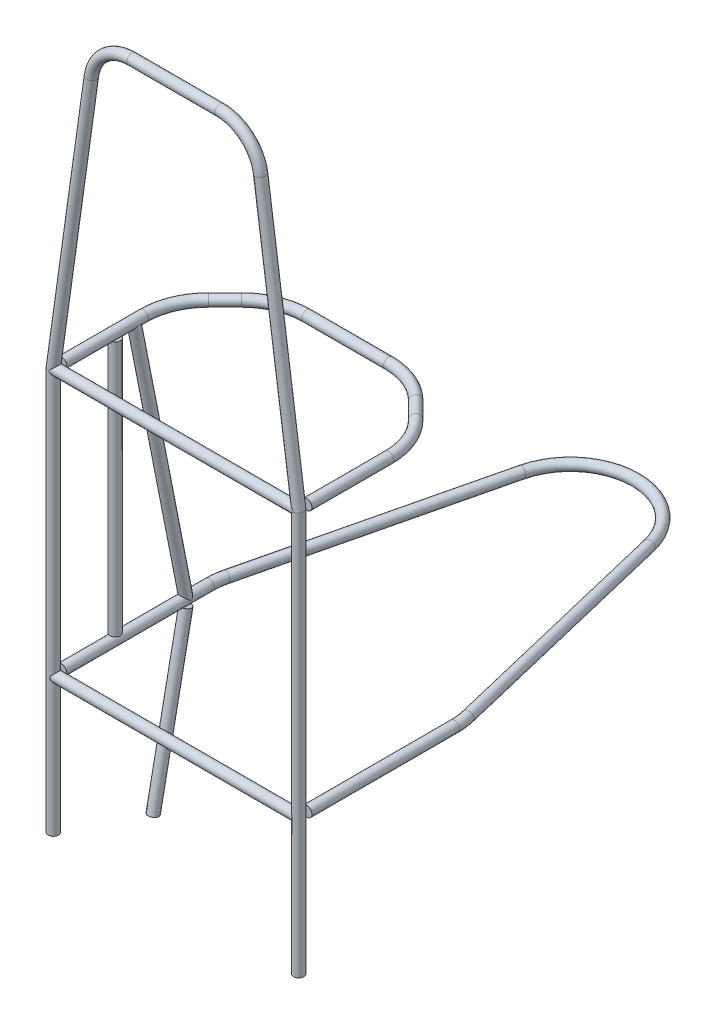
SolidWorks part; units mm, degrees
ref_plane "前视基准面" through (0, 0, 0) normal (0, 0, 1) x (1, 0, 0)
ref_plane "上视基准面" through (0, 0, 0) normal (0, 1, 0) x (1, 0, 0)
ref_plane "右视基准面" through (0, 0, 0) normal (1, 0, 0) x (0, 0, -1)
sketch "草图7" plane through (0, 0, 0) normal (0, 1, 0) x (1, 0, 0)
  line L0 (-295.5792, 18.414) -> (-155.5792, 601.556)
  line L1 (0, 0) -> (0, 80.2644) construction
  line L2 (295.5792, 18.414) -> (155.5792, 601.556)
  line L3 (-300, 0) -> (300, 0) construction
  line L4 (-300, -18.9372) -> (-300, -380)
  line L5 (300, -18.9372) -> (300, -380)
  arc A0 (155.5792, 601.556) -> (-155.5792, 601.556) centre (0, 564.2047) ccw
  arc A1 (-300, -18.9372) -> (-295.5792, 18.414) centre (-140, -18.9372) cw
  arc A2 (295.5792, 18.414) -> (300, -18.9372) centre (140, -18.9372) cw
  dimension "D1" = 160
  dimension "D2" = 27
  dimension "D6" = 160
  dimension "D7" = 160
  dimension "D3" = 380
  dimension "D4" = 600
  dimension "D5" = 380
sweep "扫描1" add path "草图7" circular profile diameter 25 parameters "D3"=25
ref_plane "基准面1" through (0, 650, 0) normal (0, 1, 0) x (1, 0, 0)
sketch "草图16" plane through (0, 650, 0) normal (0, 1, 0) x (1, 0, 0)
  line L0 (-300, -380) -> (-300, -180)
  line L1 (-253.1371, -66.8629) -> (-213.1371, -26.8629)
  line L2 (-100, 20) -> (100, 20)
  line L3 (213.1371, -26.8629) -> (253.1371, -66.8629)
  line L4 (300, -180) -> (300, -380)
  line L5 (-300, -380) -> (300, -380) construction
  line L6 (-270.4863, -544.0023) -> (-254.1487, -544.0023)
  line L8 (-300, -180) -> (300, -180) construction
  line L9 (0, 0) -> (0, 20) construction
  arc A0 (-300, -180) -> (-253.1371, -66.8629) centre (-140, -180) cw
  arc A1 (253.1371, -66.8629) -> (300, -180) centre (140, -180) cw
  arc A2 (-100, 20) -> (-213.1371, -26.8629) centre (-100, -140) ccw
  arc A3 (213.1371, -26.8629) -> (100, 20) centre (100, -140) ccw
  dimension "D3" = 160
  dimension "D4" = 160
  dimension "D5" = 160
  dimension "D6" = 160
  dimension "D1" = 300
  dimension "D2" = 400
  dimension "D7" = 200
  dimension "D8" = 300
  dimension "D9" = 380
sweep "扫描2" add path "草图16" circular profile diameter 25 parameters "D3"=25
ref_plane "基准面2" through (-300, 0, 0) normal (1, 0, 0) x (0, 0, -1)
sketch "草图62" plane through (-300, 0, 0) normal (1, 0, 0) x (0, 0, -1)
  line L0 (-203.1129, 648.3242) -> (-75.5151, 0)
sweep "扫描4" add path "草图62" circular profile diameter 25 parameters "D3"=25
ref_plane "基准面3" through (0, 0, 400) normal (0, 0, 1) x (1, 0, 0)
sketch "草图71" plane through (0, 0, 400) normal (0, 0, 1) x (1, 0, 0)
  line L0 (-300, -334.0844) -> (-300, 650)
  line L1 (-300, 650) -> (-206.9934, 1313.8742)
  line L2 (-107.9605, 1400) -> (107.9605, 1400)
  line L3 (206.9934, 1313.8742) -> (300, 650)
  line L4 (300, 650) -> (300, -334.0844)
  line L5 (0, 0) -> (0, 1657.6466) construction
  line L7 (343.75, 650) -> (-343.75, 650) construction
  line L8 (-300, -371.25) -> (-300, 371.25) construction
  arc A2 (-107.9605, 1400) -> (-206.9934, 1313.8742) centre (-107.9605, 1300) ccw
  arc A3 (206.9934, 1313.8742) -> (107.9605, 1400) centre (107.9605, 1300) ccw
  point P2 (-206.9934, 1313.8742)
  dimension "D1" = 100
  dimension "D2" = 100
  dimension "D3" = 750
sweep "扫描5" add path "草图71" circular profile diameter 25 parameters "D3"=25
sketch "草图72" plane through (-300, 0, 0) normal (1, 0, 0) x (0, 0, -1)
  line L0 (-75.8114, -15.8442) -> (-156.1001, -417.8459)
sweep "扫描6" add path "草图72" circular profile diameter 25 parameters "D3"=25
sketch "草图89" plane through (-300, 0, 0) normal (1, 0, 0) x (0, 0, -1)
  line L0 (-248.7692, 12.5) -> (-248.7692, 637.5)
  line L1 (-380, 637.5) -> (-213.7224, 637.5) construction
  line L2 (-90.7151, 12.5) -> (-380, 12.5) construction
sweep "扫描7" add path "草图89" circular profile diameter 25 parameters "D3"=25
sketch "草图104" plane through (0, 0, 400) normal (0, 0, 1) x (1, 0, 0)
  line L0 (-300, 650) -> (300, 650)
  line L1 (-312.5, 650.8714) -> (-287.5, 649.1286) construction
  line L2 (312.5, 650.8714) -> (287.5, 649.1286) construction
sweep "扫描8" add path "草图104" circular profile diameter 25 parameters "D3"=25
sketch "草图113" plane through (0, 0, 400) normal (0, 0, 1) x (1, 0, 0)
  line L0 (-295.5792, 0) -> (295.5792, 0)
  line L1 (343.75, 0) -> (-343.75, 0) construction
sweep "扫描9" add path "草图113" circular profile diameter 25 parameters "D3"=25
